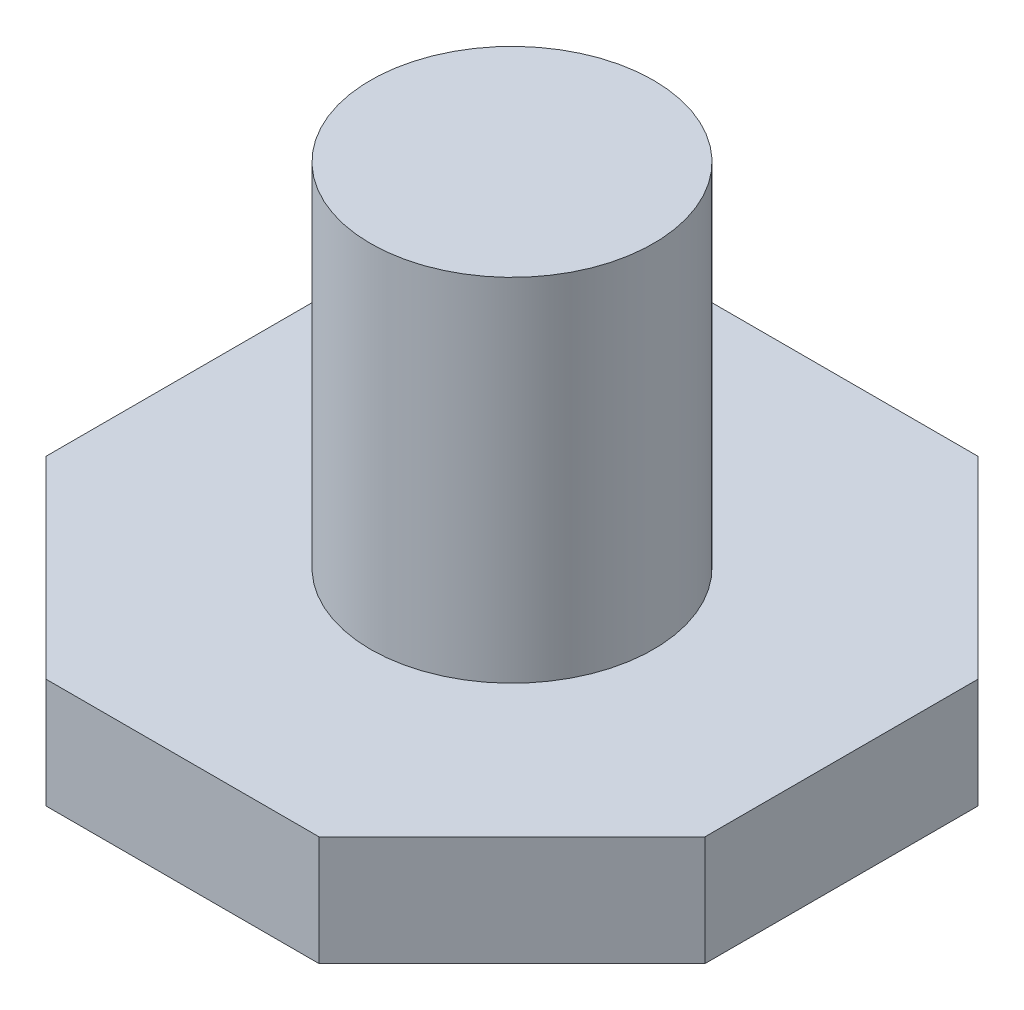
SolidWorks part; units mm, degrees
material "ABS"
ref_plane "Front Plane" through (0, 0, 0) normal (0, 0, 1) x (1, 0, 0)
ref_plane "Top Plane" through (0, 0, 0) normal (0, 1, 0) x (1, 0, 0)
ref_plane "Right Plane" through (0, 0, 0) normal (1, 0, 0) x (0, 0, -1)
sketch "Sketch1" plane through (0, 0, 0) normal (0, 1, 0) x (1, 0, 0)
  line L1 (4.7625, -1.9727) -> (4.7625, 1.9727)
  line L2 (4.7625, 1.9727) -> (1.9727, 4.7625)
  line L3 (1.9727, 4.7625) -> (-1.9727, 4.7625)
  line L4 (-1.9727, 4.7625) -> (-4.7625, 1.9727)
  line L5 (-4.7625, 1.9727) -> (-4.7625, -1.9727)
  line L6 (-4.7625, -1.9727) -> (-1.9727, -4.7625)
  line L7 (-1.9727, -4.7625) -> (1.9727, -4.7625)
  line L8 (1.9727, -4.7625) -> (4.7625, -1.9727)
  circle A0 centre (0, 0) radius 4.7625 construction
  dimension "D1" = 9.525
extrude "Boss-Extrude1" add sketch "Sketch1" along normal blind 1.5875
sketch "Sketch2" plane through (0, 1.5875, 0) normal (0, 1, 0) x (1, 0, 0)
  circle A0 centre (0, 0) radius 2.0447
  dimension "D1" = 4.0894
extrude "Boss-Extrude3" add sketch "Sketch2" along normal blind 5.08
